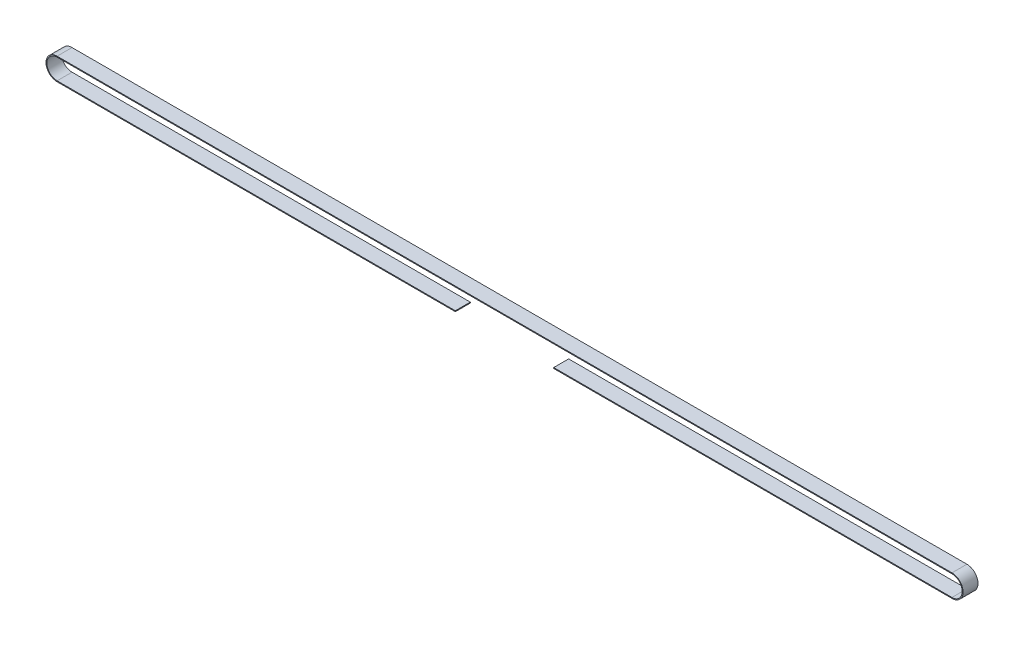
SolidWorks part; units mm, degrees
ref_plane "Front Plane" through (0, 0, 0) normal (0, 0, 1) x (1, 0, 0)
ref_plane "Top Plane" through (0, 0, 0) normal (0, 1, 0) x (1, 0, 0)
ref_plane "Right Plane" through (0, 0, 0) normal (1, 0, 0) x (0, 0, -1)
sketch "Sketch1" plane through (0, 0, 0) normal (0, 0, 1) x (1, 0, 0)
  line L0 (-254.75, 0) -> (254.75, 0) construction
  line L1 (-254.75, 5.82) -> (254.75, 5.82)
  line L2 (-254.75, -5.82) -> (254.75, -5.82)
  arc A0 (-254.75, 5.82) -> (-254.75, -5.82) centre (-254.75, 0) ccw
  arc A1 (254.75, -5.82) -> (254.75, 5.82) centre (254.75, 0) ccw
  point P3 (0, 0)
  dimension "D1" = 509.5
  dimension "D2" = 11.64
sketch "Sketch2" plane through (0, 0, 0) normal (1, 0, 0) x (0, 0, -1)
  line L1 (-4.25, 6.32) -> (4.25, 6.32)
  line L2 (-4.25, 6.32) -> (-4.25, 5.82)
  line L3 (-4.25, 5.82) -> (4.25, 5.82)
  line L4 (4.25, 6.32) -> (4.25, 5.82)
  point P4 (0, 5.82)
  dimension "D1" = 0.5
  dimension "D2" = 8.5
sweep "Sweep1" add profiles "Sketch2" path "Sketch1"
sketch "Sketch3" plane through (0, 0, 0) normal (0, 0, 1) x (1, 0, 0)
  line L1 (-28, -40) -> (28, -40)
  line L2 (-28, -40) -> (-28, 0)
  line L3 (-28, 0) -> (28, 0)
  line L4 (28, -40) -> (28, 0)
  dimension "D1" = 56
  dimension "D2" = 40
extrude "Cut-Extrude1" cut sketch "Sketch3" against normal through all both and the other way through all
